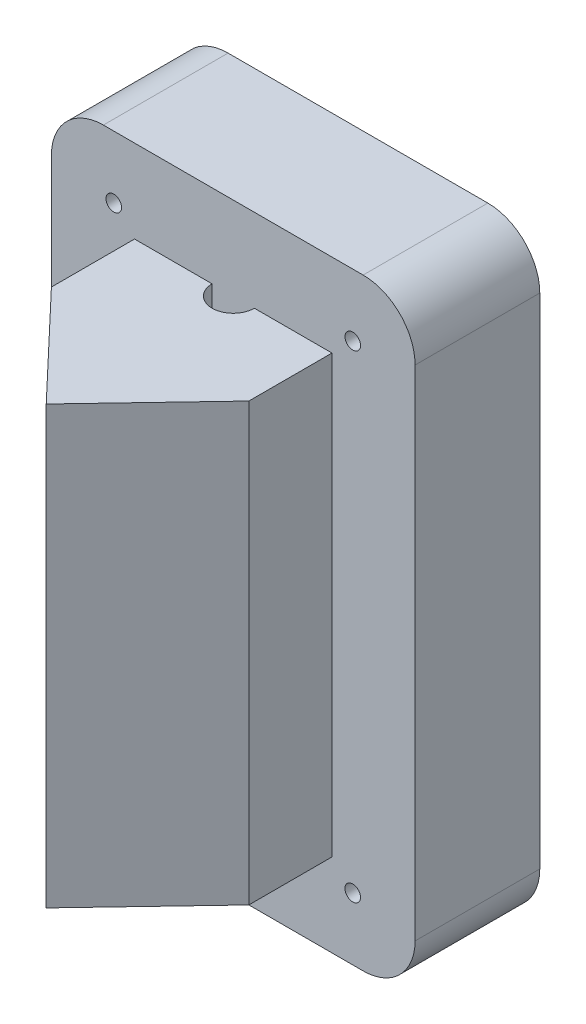
SolidWorks part; units mm, degrees
ref_plane "Ön Düzlem" through (0, 0, 0) normal (0, 0, 1) x (1, 0, 0)
ref_plane "Üst Düzlem" through (0, 0, 0) normal (0, 1, 0) x (1, 0, 0)
ref_plane "Sağ Düzlem" through (0, 0, 0) normal (1, 0, 0) x (0, 0, -1)
sketch "Çizim4" plane through (0, 0, 0) normal (0, 0, 1) x (1, 0, 0)
  line L1 (0, 0) -> (-175, 0)
  line L2 (0, 0) -> (0, 290)
  line L3 (0, 290) -> (-175, 290)
  line L4 (-175, 0) -> (-175, 290)
  dimension "D1" = 175
  dimension "D2" = 290
extrude "Yükseklik-Ekstrüzyon5" add sketch "Çizim4" along normal blind 60
fillet "Radyus4" radius 25 4 edges at (-175, 0, 30) (0, 0, 30) (0, 290, 30) (-175, 290, 30)
sketch "Çizim8" plane through (0, 0, 60) normal (0, 0, 1) x (1, 0, 0)
  circle A0 centre (-145, 30) radius 3.75
  circle A1 centre (-30, 30) radius 3.75
  circle A2 centre (-145, 260) radius 3.75
  circle A3 centre (-30, 260) radius 3.75
  dimension "D3" = 7.5
  dimension "D5" = 7.5
  dimension "D7" = 7.5
  dimension "D8" = 7.5
extrude "Kes-Ekstrüzyon2" cut sketch "Çizim8" against normal through all and the other way through all
sketch "Çizim9" plane through (0, 0, 60) normal (0, 0, 1) x (1, 0, 0)
  line L0 (-135, 40) -> (-40, 40)
  line L4 (-135, 40) -> (-135, 250)
  line L5 (-135, 250) -> (-40, 250)
  line L6 (-40, 250) -> (-40, 40)
  point P4 (-87.5, 40)
extrude "Yükseklik-Ekstrüzyon8" add sketch "Çizim9" along normal blind 90
sketch "Çizim11" plane through (0, 250, 0) normal (0, 1, 0) x (1, 0, 0)
  line L0 (-135, -100) -> (-87.5, -150)
  line L1 (-135, -150) -> (-135, -60) construction
  line L2 (-40, -150) -> (-135, -150) construction
  line L3 (-87.5, -150) -> (-40, -100)
  line L4 (-40, -150) -> (-40, -60) construction
  line L7 (-40, -100) -> (-40, -150)
  line L8 (-40, -150) -> (-87.5, -150)
  line L9 (-87.5, -150) -> (-135, -150)
  line L10 (-135, -150) -> (-135, -100)
  line L11 (-40, -150) -> (-87.5, -150)
  line M5 (-135, -60) -> (-135, -150)
  line M6 (-135, -150) -> (-40, -150)
  line M7 (-40, -150) -> (-40, -60)
extrude "Kes-Ekstrüzyon4" cut sketch "Çizim11" against normal through all contours L3 M6 M7 | L0 M5 M6
sketch "Çizim16" plane through (0, 250, 0) normal (0, 1, 0) x (1, 0, 0)
  line L0 (-77.3297, -60) -> (-97.6703, -60)
  line L4 (-40, -60) -> (-135, -60) construction
  arc A2 (-97.6703, -60) -> (-77.3297, -60) centre (-87.5, -60) ccw
  dimension "D1" = 20.3407
extrude "Kes-Ekstrüzyon8" cut sketch "Çizim16" against normal through all
